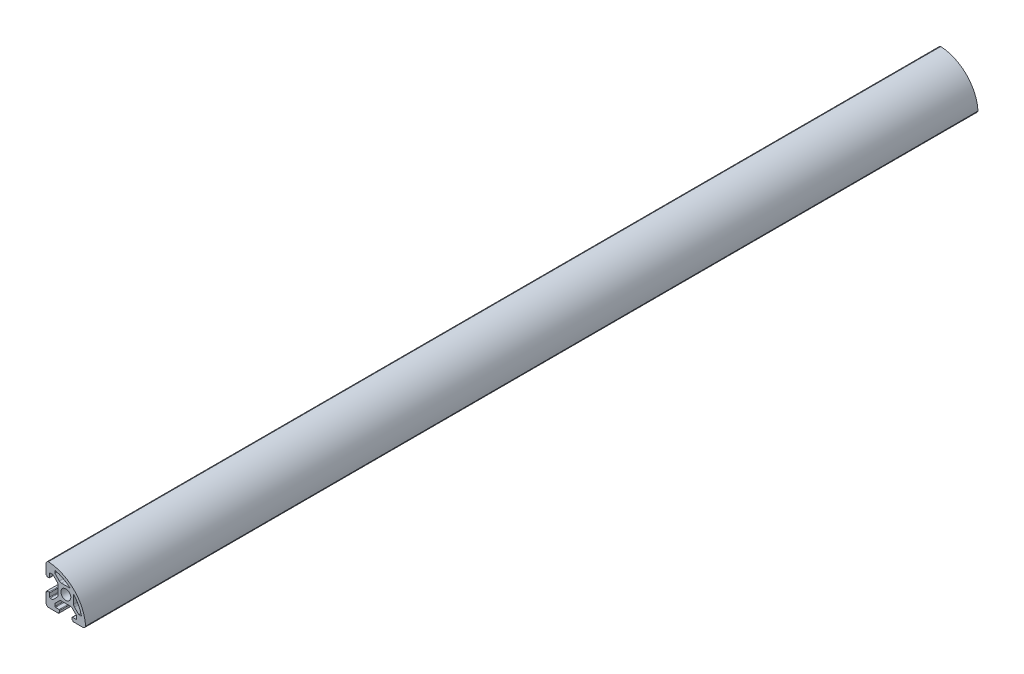
SolidWorks part; units mm, degrees
ref_plane "前视基准面" through (0, 0, 0) normal (0, 0, 1) x (1, 0, 0)
ref_plane "上视基准面" through (0, 0, 0) normal (0, 1, 0) x (1, 0, 0)
ref_plane "右视基准面" through (0, 0, 0) normal (1, 0, 0) x (0, 0, -1)
sketch "草图1" plane through (0, 0, 0) normal (0, 0, 1) x (1, 0, 0)
  line L14 (2.0848, 3.8649) -> (-2.342, 3.8649)
  line L15 (-3.4027, 4.3042) -> (-5.6233, 6.5249)
  line L16 (-5.6233, 6.5249) -> (-5.6233, 7.8649)
  line L22 (-10.1233, 8.4649) -> (-10.1233, 3.5649)
  line L23 (-10.1233, 3.5649) -> (-9.8233, 3.5649)
  line L24 (-9.6233, 3.3649) -> (-9.6233, 3.0649)
  line L25 (-9.6233, 3.0649) -> (-8.6233, 3.0649)
  line L26 (-8.3233, 3.3649) -> (-8.3233, 5.1649)
  line L27 (-8.0233, 5.4649) -> (-6.6833, 5.4649)
  line L28 (-6.6833, 5.4649) -> (-4.4627, 3.2442)
  line L29 (-4.0233, 2.1836) -> (-4.0233, -2.2538)
  line L30 (-4.4627, -3.3144) -> (-6.6833, -5.5351)
  line L31 (-6.6833, -5.5351) -> (-8.0233, -5.5351)
  line L32 (-8.3233, -5.2351) -> (-8.3233, -3.4351)
  line L33 (-8.6233, -3.1351) -> (-9.6233, -3.1351)
  line L34 (-9.6233, -3.1351) -> (-9.6233, -3.4351)
  line L35 (-9.8233, -3.6351) -> (-10.1233, -3.6351)
  line L36 (-10.1233, -3.6351) -> (-10.1233, -8.5351)
  line L37 (-8.6233, -10.0351) -> (-3.7233, -10.0351)
  line L38 (-3.7233, -10.0351) -> (-3.7233, -9.7351)
  line L39 (-3.5233, -9.5351) -> (-3.2233, -9.5351)
  line L40 (-3.2233, -9.5351) -> (-3.2233, -8.5351)
  line L41 (-3.5233, -8.2351) -> (-5.3233, -8.2351)
  line L42 (-5.6233, -7.9351) -> (-5.6233, -6.5951)
  line L43 (-5.6233, -6.5951) -> (-3.4027, -4.3744)
  line L44 (-2.342, -3.9351) -> (2.0953, -3.9351)
  line L45 (3.156, -4.3744) -> (5.3767, -6.5951)
  line L46 (5.3767, -6.5951) -> (5.3767, -7.9351)
  line L47 (5.0767, -8.2351) -> (3.2767, -8.2351)
  line L48 (2.9767, -8.5351) -> (2.9767, -9.5351)
  line L49 (2.9767, -9.5351) -> (3.2767, -9.5351)
  line L50 (3.4767, -9.7351) -> (3.4767, -10.0351)
  line L51 (3.4767, -10.0351) -> (8.3767, -10.0351)
  line L57 (7.7767, -5.5351) -> (6.4367, -5.5351)
  line L58 (6.4367, -5.5351) -> (4.216, -3.3144)
  line L59 (3.7767, -2.2538) -> (3.7767, 2.1836)
  circle A0 centre (-0.1233, -0.0351) radius 2.5
  arc A1 (7.8202, -5.5319) -> (3.7767, 2.1731) centre (-10.1233, -10.0351) ccw
  arc A2 (2.0848, 3.8649) -> (-5.6202, 7.9085) centre (-10.1233, -10.0351) ccw
  arc A9 (-3.4027, 4.3042) -> (-2.342, 3.8649) centre (-2.342, 5.3649) ccw
  arc A10 (-5.3233, 8.1649) -> (-5.6233, 7.8649) centre (-5.3233, 7.8649) ccw
  arc A13 (-8.6233, 9.9649) -> (-10.1233, 8.4649) centre (-8.6233, 8.4649) ccw
  arc A14 (-9.6233, 3.3649) -> (-9.8233, 3.5649) centre (-9.8233, 3.3649) ccw
  arc A15 (-8.6233, 3.0649) -> (-8.3233, 3.3649) centre (-8.6233, 3.3649) ccw
  arc A16 (-8.0233, 5.4649) -> (-8.3233, 5.1649) centre (-8.0233, 5.1649) ccw
  arc A17 (-4.0233, 2.1836) -> (-4.4627, 3.2442) centre (-5.5233, 2.1836) ccw
  arc A18 (-4.4627, -3.3144) -> (-4.0233, -2.2538) centre (-5.5233, -2.2538) ccw
  arc A19 (-8.3233, -5.2351) -> (-8.0233, -5.5351) centre (-8.0233, -5.2351) ccw
  arc A20 (-8.3233, -3.4351) -> (-8.6233, -3.1351) centre (-8.6233, -3.4351) ccw
  arc A21 (-9.8233, -3.6351) -> (-9.6233, -3.4351) centre (-9.8233, -3.4351) ccw
  arc A22 (-10.1233, -8.5351) -> (-8.6233, -10.0351) centre (-8.6233, -8.5351) ccw
  arc A23 (-3.5233, -9.5351) -> (-3.7233, -9.7351) centre (-3.5233, -9.7351) ccw
  arc A24 (-3.2233, -8.5351) -> (-3.5233, -8.2351) centre (-3.5233, -8.5351) ccw
  arc A25 (-5.6233, -7.9351) -> (-5.3233, -8.2351) centre (-5.3233, -7.9351) ccw
  arc A26 (-2.342, -3.9351) -> (-3.4027, -4.3744) centre (-2.342, -5.4351) ccw
  arc A27 (3.156, -4.3744) -> (2.0953, -3.9351) centre (2.0953, -5.4351) ccw
  arc A28 (5.0767, -8.2351) -> (5.3767, -7.9351) centre (5.0767, -7.9351) ccw
  arc A29 (3.2767, -8.2351) -> (2.9767, -8.5351) centre (3.2767, -8.5351) ccw
  arc A30 (3.4767, -9.7351) -> (3.2767, -9.5351) centre (3.2767, -9.7351) ccw
  arc A31 (8.3767, -10.0351) -> (9.8767, -8.5351) centre (8.3767, -8.5351) ccw
  arc A34 (7.7767, -5.5351) -> (7.8202, -5.5319) centre (7.7767, -5.2351) ccw
  arc A35 (3.7767, -2.2538) -> (4.216, -3.3144) centre (5.2767, -2.2538) ccw
  arc A37 (9.8419, -8.8562) -> (-8.9445, 9.9301) centre (-10.1233, -10.0351) ccw
extrude "凸台-拉伸1" add sketch "草图1" along normal blind 450 contours A31 A37 A13 L22 L23 A14 L24 L25 A15 L26 A16 L27 L28 A17 L29 A18 L30 L31 A19 L32 A20 L33 L34 A21 L35 L36 A22 L37 L38 A23 L39 L40 A24 L41 A25 L42 L43 A26 L44 A27 L45 L46 A28 L47 A29 L48 L49 A30 L50 L51
